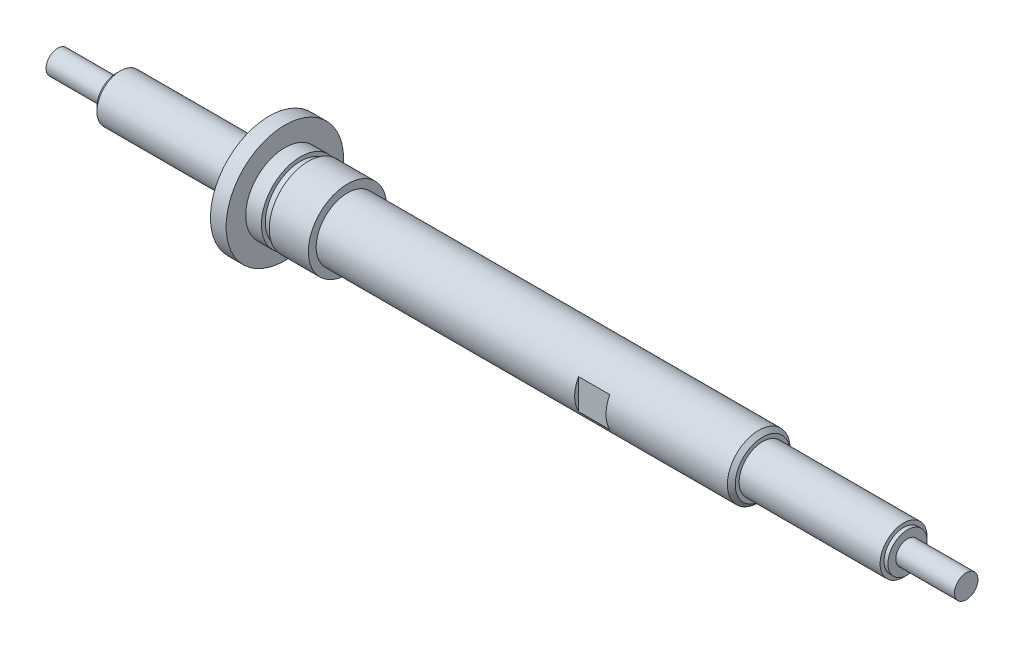
SolidWorks part; units mm, degrees
ref_plane "前视基准面" through (0, 0, 0) normal (0, 0, 1) x (1, 0, 0)
ref_plane "上视基准面" through (0, 0, 0) normal (0, 1, 0) x (1, 0, 0)
ref_plane "右视基准面" through (0, 0, 0) normal (1, 0, 0) x (0, 0, -1)
sketch "草图1" plane through (0, 0, 0) normal (1, 0, 0) x (0, 0, -1)
  circle A0 centre (0, 0) radius 4
  dimension "D1" = 8
extrude "凸台-拉伸1" add sketch "草图1" along normal blind 1
sketch "草图2" plane through (0, 0, 0) normal (-1, 0, 0) x (0, 0, 1)
  circle A0 centre (0, 0) radius 3
  dimension "D1" = 6
extrude "凸台-拉伸2" add sketch "草图2" along normal blind 9
sketch "草图3" plane through (-9, 0, 0) normal (-1, 0, 0) x (0, 0, 1)
  circle A0 centre (0, 0) radius 3
  dimension "D1" = 6
extrude "凸台-拉伸3" add sketch "草图3" along normal blind 17
sketch "草图4" plane through (1, 0, 0) normal (1, 0, 0) x (0, 0, -1)
  circle A0 centre (0, 0) radius 7.5
  dimension "D1" = 15
extrude "凸台-拉伸4" add sketch "草图4" along normal blind 2
sketch "草图5" plane through (3, 0, 0) normal (1, 0, 0) x (0, 0, -1)
  circle A0 centre (0, 0) radius 5
  dimension "D1" = 10
extrude "凸台-拉伸5" add sketch "草图5" along normal blind 8
cosmetic thread "装饰螺纹线2" parameters "D1"=5, "D2"=10
cosmetic thread "装饰螺纹线3" parameters "D1"=5, "D2"=9
cosmetic thread "装饰螺纹线4" parameters "D1"=5.2, "D2"=9
sketch "草图6" plane through (11, 0, 0) normal (1, 0, 0) x (0, 0, -1)
  circle A0 centre (0, 0) radius 4
  dimension "D1" = 8
extrude "凸台-拉伸6" add sketch "草图6" along normal blind 53
sketch "草图7" plane through (64, 0, 0) normal (1, 0, 0) x (0, 0, -1)
  circle A0 centre (0, 0) radius 3
  dimension "D1" = 6
extrude "凸台-拉伸7" add sketch "草图7" along normal blind 9
sketch "草图8" plane through (73, 0, 0) normal (1, 0, 0) x (0, 0, -1)
  circle A0 centre (0, 0) radius 3
  dimension "D1" = 6
extrude "凸台-拉伸8" add sketch "草图8" along normal blind 17
chamfer "倒角1" distance 0.5 angle 45 1 edges at (64, 0, -4)
chamfer "倒角2" distance 0.5 angle 45 1 edges at (0, 0, -4)
sketch "草图11" plane through (3, 0, 0) normal (1, 0, 0) x (0, 0, -1)
  circle A0 centre (0, 0) radius 4.5
  circle A1 centre (0, 0) radius 5
  dimension "D1" = 9
  dimension "D2" = 10
extrude "切除-拉伸2" cut sketch "草图11" along normal blind 1 from offset 2
sketch "草图12" plane through (0, 0, 0) normal (0, 1, 0) x (1, 0, 0)
  line L0 (63.5, 4) -> (11, 4) construction
  line L1 (44, 4) -> (48, 4)
  line L2 (44, 4) -> (44, 3.5)
  line L3 (44, 3.5) -> (48, 3.5)
  line L4 (48, 4) -> (48, 3.5)
  line L5 (64, 0) -> (50.1879, 0) construction
  line L6 (64, -3) -> (64, 3) construction
  line L7 (64, -3.5) -> (64, 3.5) construction
  line L8 (48, -4) -> (48, -3.5)
  line L9 (44, -3.5) -> (48, -3.5)
  line L10 (44, -4) -> (48, -4)
  line L11 (44, -4) -> (44, -3.5)
  dimension "D1" = 20
  dimension "D2" = 4
  dimension "D3" = 7
extrude "切除-拉伸3" cut sketch "草图12" against normal mid plane 10
sketch "草图14" plane through (90, 0, 0) normal (1, 0, 0) x (0, 0, -1)
  circle A0 centre (0, 0) radius 3
  circle A1 centre (0, 0) radius 1.5
  dimension "D1" = 6
  dimension "D2" = 3
extrude "切除-拉伸5" cut sketch "草图14" against normal blind 7.5
cosmetic thread "装饰螺纹线5" parameters "D1"=3.5, "D2"=2
ref_plane "基准面1" through (32, 0, 0) normal (1, 0, 0) x (0, 0, -1)
sketch "草图15" plane through (82.5, 0, 0) normal (1, 0, 0) x (0, 0, -1)
  circle A0 centre (0, 0) radius 2.5
  circle A1 centre (0, 0) radius 3
  dimension "D1" = 5
  dimension "D2" = 6
extrude "切除-拉伸6" cut sketch "草图15" against normal blind 0.5
mirror "镜向2" about plane through (32, 0, 0) normal (1, 0, 0) of "切除-拉伸5", "切除-拉伸6"
